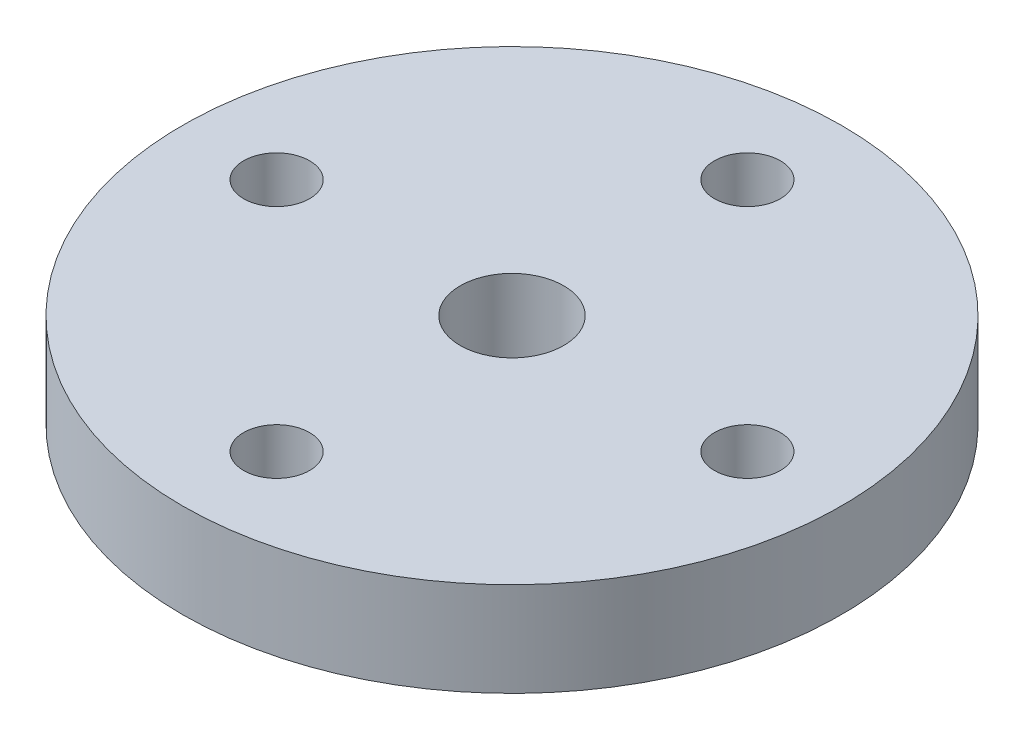
SolidWorks part; units mm, degrees
ref_plane "Front Plane" through (0, 0, 0) normal (0, 0, 1) x (1, 0, 0)
ref_plane "Top Plane" through (0, 0, 0) normal (0, 1, 0) x (1, 0, 0)
ref_plane "Right Plane" through (0, 0, 0) normal (1, 0, 0) x (0, 0, -1)
sketch "Sketch1" plane through (0, 0, 0) normal (0, 1, 0) x (1, 0, 0)
  line L0 (0, 7.5) -> (0, -7.5) construction
  line L1 (-7.5, 0) -> (7.5, 0) construction
  circle A0 centre (0, 0) radius 10.5
  circle A1 centre (0, 0) radius 1.65
  circle A2 centre (-7.5, 0) radius 1.05
  circle A3 centre (0, 7.5) radius 1.05
  circle A4 centre (7.5, 0) radius 1.05
  circle A5 centre (0, -7.5) radius 1.05
  point P7 (0, 0)
  point P10 (0, 0)
  dimension "D1" = 21
  dimension "D2" = 3.3
  dimension "D5" = 2.1
  dimension "D3" = 15
  dimension "D4" = 15
extrude "Boss-Extrude1" add sketch "Sketch1" along normal blind 3
